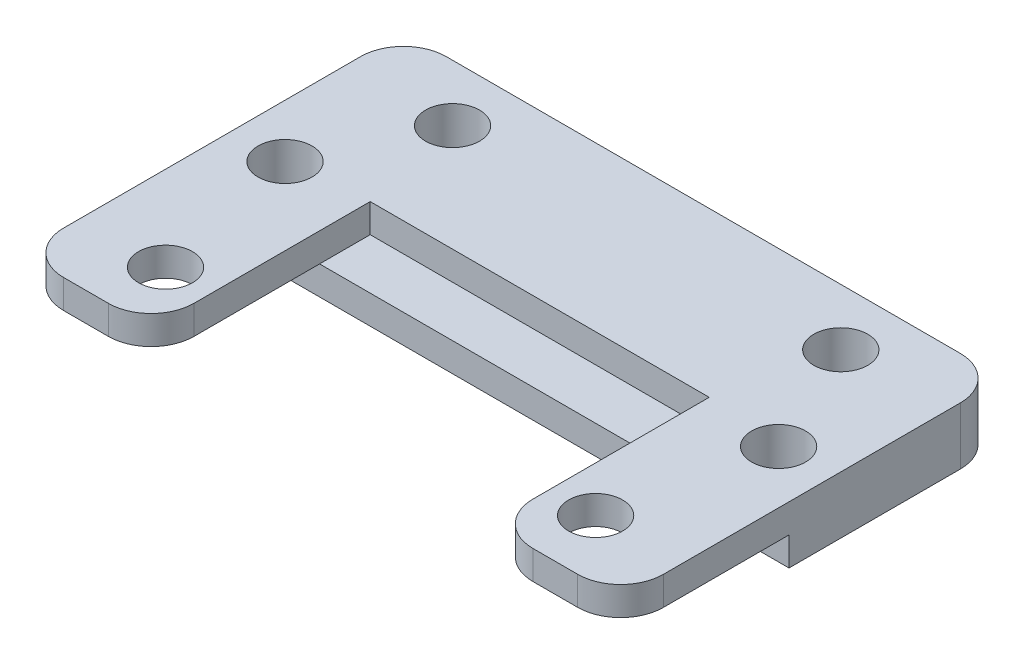
SolidWorks part; units mm, degrees
ref_plane "Front Plane" through (0, 0, 0) normal (0, 0, 1) x (1, 0, 0)
ref_plane "Top Plane" through (0, 0, 0) normal (0, 1, 0) x (1, 0, 0)
ref_plane "Right Plane" through (0, 0, 0) normal (1, 0, 0) x (0, 0, -1)
sketch "Sketch1" plane through (0, 80.955, 0) normal (0, 1, 0) x (1, 0, 0)
  line L1 (86.1651, -156.7322) -> (116.6451, -156.7322)
  line L2 (83.6251, -159.2722) -> (83.6251, -169.4322)
  line L3 (83.6251, -169.4322) -> (119.1851, -169.4322)
  line L4 (119.1851, -159.2722) -> (119.1851, -169.4322)
  line L5 (65.9051, -188.5672) -> (136.9051, -188.5672) construction
  line L6 (115.9051, -170.0672) -> (86.9051, -170.0672) construction
  arc A0 (116.6451, -156.7322) -> (119.1851, -159.2722) centre (116.6451, -159.2722) cw
  arc A1 (86.1651, -156.7322) -> (83.6251, -159.2722) centre (86.1651, -159.2722) ccw
  circle A2 centre (116.0369, -166.899) radius 1.6 construction
  circle A3 centre (112.9147, -160.0901) radius 1.6 construction
  circle A4 centre (89.8955, -160.0901) radius 1.6 construction
  circle A5 centre (86.7734, -166.899) radius 1.6 construction
  circle A6 centre (116.0369, -166.899) radius 1.6
  circle A7 centre (112.9147, -160.0901) radius 1.6
  circle A8 centre (89.8955, -160.0901) radius 1.6
  circle A9 centre (86.7734, -166.899) radius 1.6
  point P6 (101.4051, -188.5672)
  point P7 (101.4051, -169.4322)
  dimension "D2" = 2.54
  dimension "D1" = 35.56
  dimension "D3" = 12.7
  dimension "D4" = 0.635
extrude "Boss-Extrude1" add sketch "Sketch1" along normal blind 3.4
sketch "Sketch2" plane through (0, 84.355, 0) normal (0, 1, 0) x (1, 0, 0)
  line L0 (77.5551, -179.4172) -> (65.9051, -179.4172) construction
  line L1 (83.6251, -169.4322) -> (91.3551, -169.4322)
  line L2 (83.6251, -169.4322) -> (83.6251, -176.8772)
  line L3 (86.1651, -179.4172) -> (88.8151, -179.4172)
  line L4 (91.3551, -169.4322) -> (91.3551, -176.8772)
  line L5 (119.1851, -169.4322) -> (111.4551, -169.4322)
  line L6 (119.1851, -169.4322) -> (119.1851, -176.8772)
  line L7 (116.6451, -179.4172) -> (113.9951, -179.4172)
  line L8 (111.4551, -169.4322) -> (111.4551, -176.8772)
  line L9 (136.9051, -179.4172) -> (125.2551, -179.4172) construction
  line L10 (88.6551, -175.8672) -> (83.6251, -175.8672) construction
  circle A0 centre (88.6551, -175.8672) radius 1.6
  arc A1 (119.1851, -176.8772) -> (116.6451, -179.4172) centre (116.6451, -176.8772) cw
  arc A2 (113.9951, -179.4172) -> (111.4551, -176.8772) centre (113.9951, -176.8772) cw
  arc A3 (88.8151, -179.4172) -> (91.3551, -176.8772) centre (88.8151, -176.8772) ccw
  arc A4 (83.6251, -176.8772) -> (86.1651, -179.4172) centre (86.1651, -176.8772) ccw
  circle A5 centre (114.1551, -175.8672) radius 1.6
  dimension "D1" = 2.54
  dimension "D2" = 3.2
  dimension "D3" = 20.1
extrude "Boss-Extrude2" add sketch "Sketch2" against normal blind 1.7
sketch "Sketch3" plane through (0, 84.355, 0) normal (0, 1, 0) x (1, 0, 0)
  line L0 (111.4551, -169.4322) -> (111.4551, -176.8772) construction
  line L1 (91.3551, -169.4322) -> (111.4551, -169.4322)
  line L2 (91.3551, -169.4322) -> (91.3551, -166.4322)
  line L3 (91.3551, -166.4322) -> (111.4551, -166.4322)
  line L4 (111.4551, -169.4322) -> (111.4551, -166.4322)
  dimension "D1" = 3
extrude "Cut-Extrude1" cut sketch "Sketch3" against normal blind 1.7
